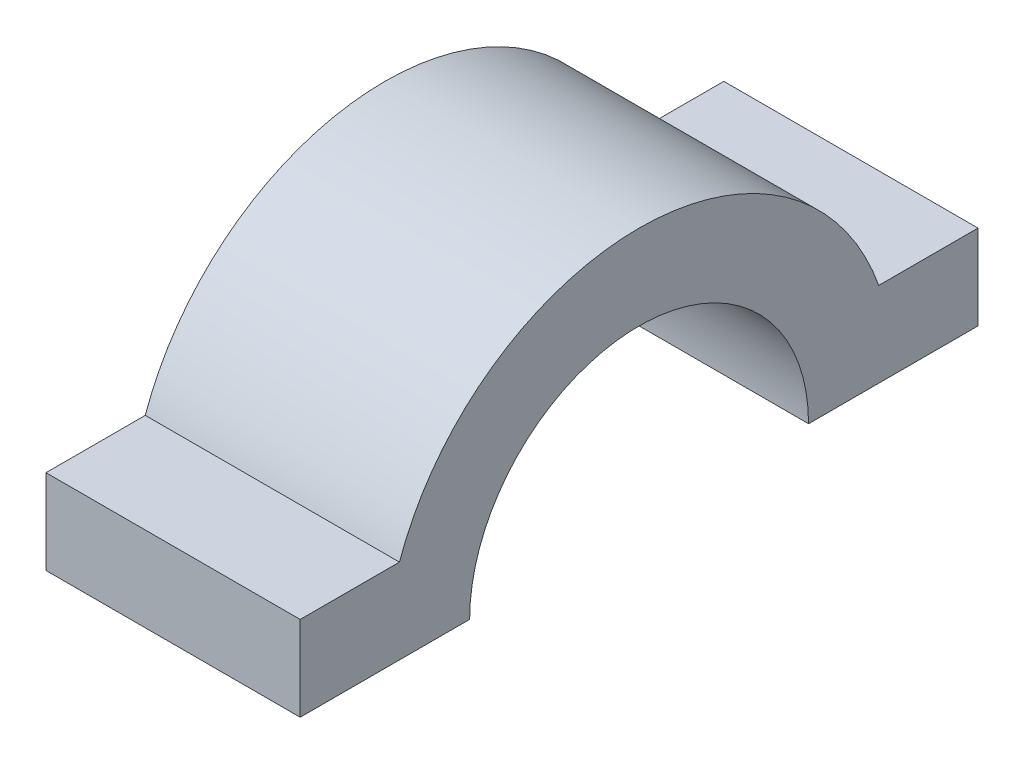
SolidWorks part; units mm, degrees
ref_plane "Alzado" through (0, 0, 0) normal (0, 0, 1) x (1, 0, 0)
ref_plane "Planta" through (0, 0, 0) normal (0, 1, 0) x (1, 0, 0)
ref_plane "Vista lateral" through (0, 0, 0) normal (1, 0, 0) x (0, 0, -1)
sketch "Croquis1" plane through (0, 0, 0) normal (1, 0, 0) x (0, 0, -1)
  line L0 (10, 0) -> (20, 0)
  line L1 (20, 0) -> (20, 5)
  line L2 (20, 5) -> (14.1421, 5)
  line L3 (-10, 0) -> (-20, 0)
  line L4 (-20, 0) -> (-20, 5)
  line L5 (-20, 5) -> (-14.1421, 5)
  arc A0 (-10, 0) -> (10, 0) centre (0, 0) cw
  arc A1 (-14.1421, 5) -> (14.1421, 5) centre (0, 0) cw
  dimension "D5" = 10
  dimension "D6" = 15
  dimension "D1" = 10
  dimension "D2" = 10
  dimension "D3" = 5
  dimension "D4" = 5
extrude "Saliente-Extruir1" add sketch "Croquis1" against normal blind 15
